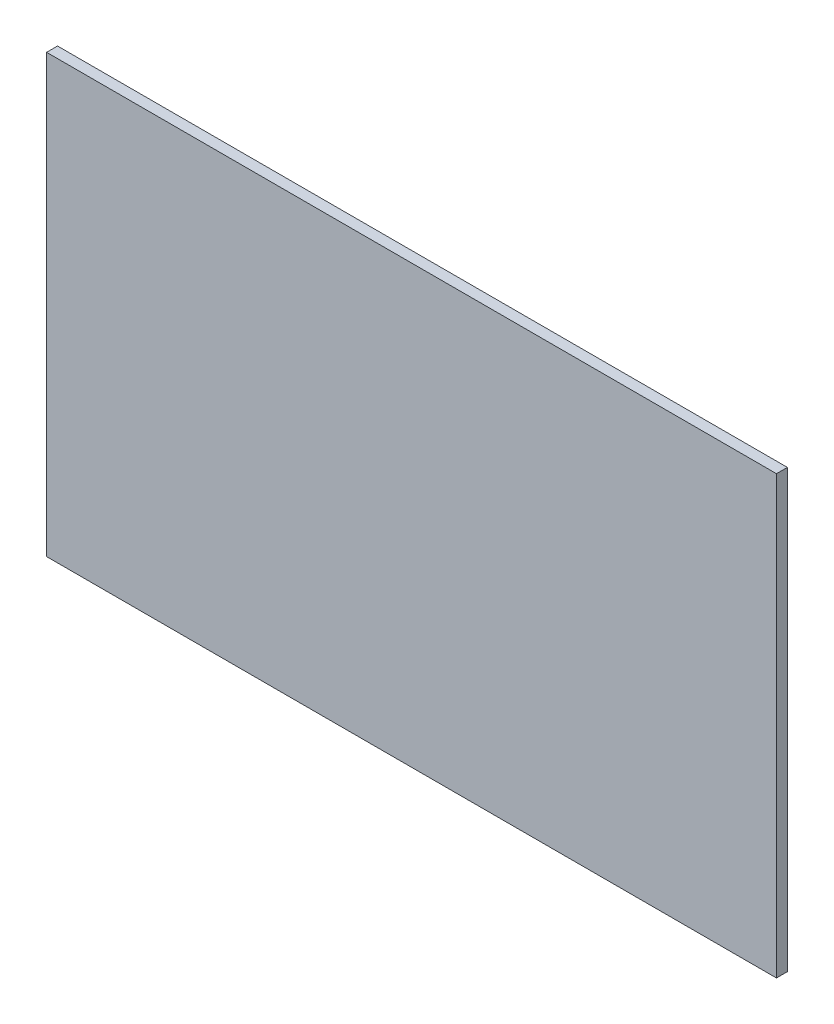
SolidWorks part; units mm, degrees
ref_plane "Спереди" through (0, 0, 0) normal (0, 0, 1) x (1, 0, 0)
ref_plane "Сверху" through (0, 0, 0) normal (0, 1, 0) x (1, 0, 0)
ref_plane "Справа" through (0, 0, 0) normal (1, 0, 0) x (0, 0, -1)
sketch "Эскиз1" plane through (0, 0, 0) normal (0, 1, 0) x (1, 0, 0)
  line L1 (0, 0) -> (167.1179, 0)
  line L2 (0, 0) -> (0, -2.5)
  line L3 (0, -2.5) -> (167.1179, -2.5)
  line L4 (167.1179, 0) -> (167.1179, -2.5)
extrude "Вытянуть1" add sketch "Эскиз1" along normal blind 100
